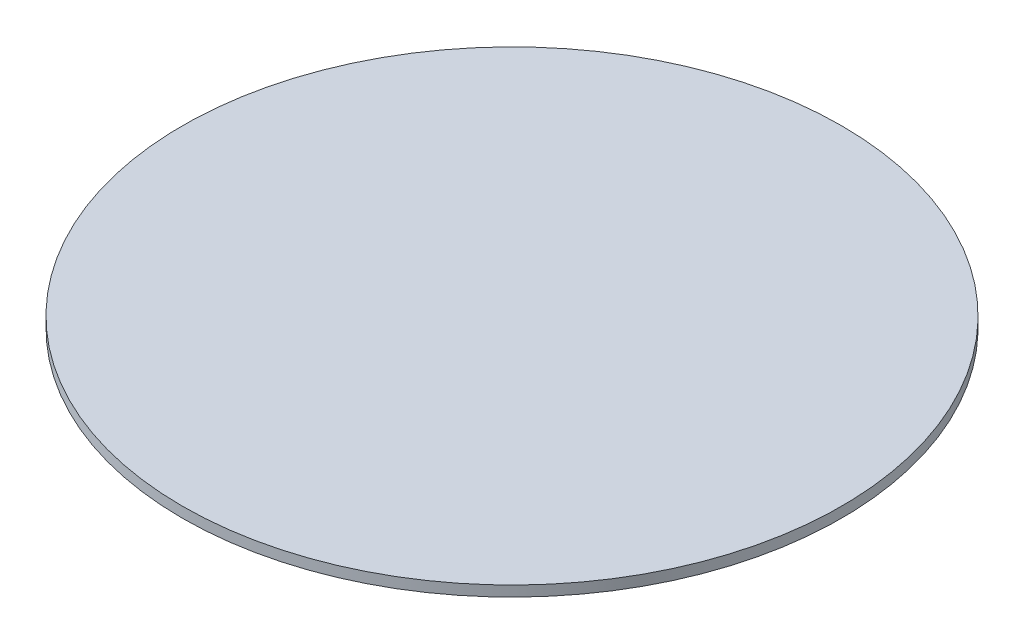
SolidWorks part; units mm, degrees
ref_plane "Front Plane" through (0, 0, 0) normal (0, 0, 1) x (1, 0, 0)
ref_plane "Top Plane" through (0, 0, 0) normal (0, 1, 0) x (1, 0, 0)
ref_plane "Right Plane" through (0, 0, 0) normal (1, 0, 0) x (0, 0, -1)
sketch "Sketch1" plane through (0, 0, 0) normal (0, 1, 0) x (1, 0, 0)
  circle A0 centre (0, 0) radius 100
  dimension "D1" = 200
extrude "Boss-Extrude1" add sketch "Sketch1" along normal blind 3.175
